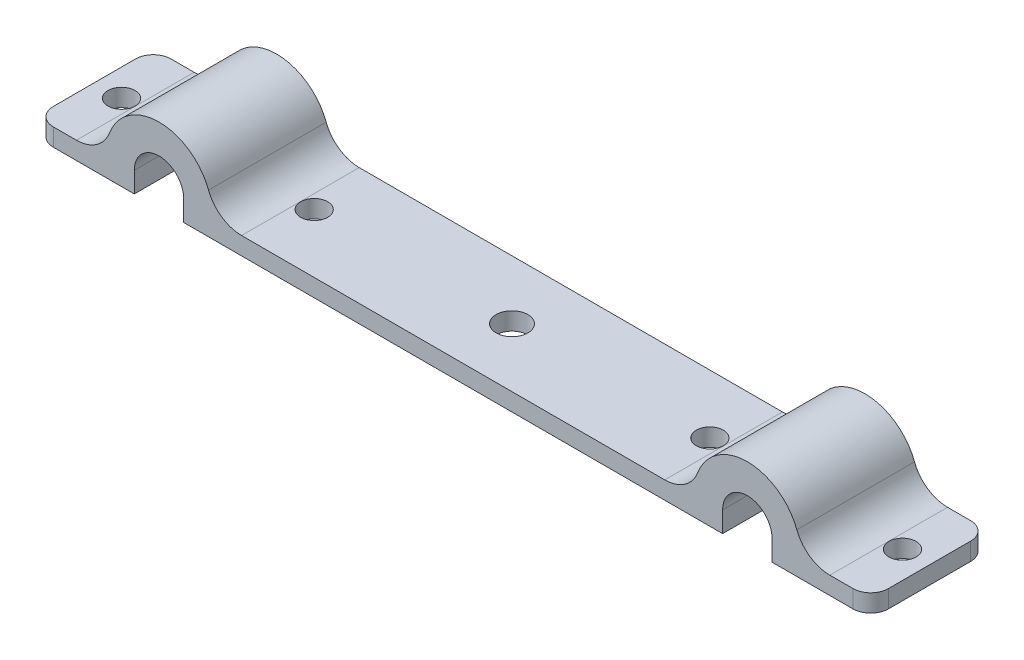
SolidWorks part; units mm, degrees
ref_plane "前视基准面" through (0, 0, 0) normal (0, 0, 1) x (1, 0, 0)
ref_plane "上视基准面" through (0, 0, 0) normal (0, 1, 0) x (1, 0, 0)
ref_plane "右视基准面" through (0, 0, 0) normal (1, 0, 0) x (0, 0, -1)
sketch "草图1" plane through (0, 0, 0) normal (0, 0, 1) x (1, 0, 0)
  line L0 (-1000, 0) -> (49000, 0) construction
  line L1 (0, -1000) -> (0, 49000) construction
  line L2 (54.2, 3.8) -> (54.2, 0.3)
  line L3 (54.2, 0.3) -> (70.9727, 0.3)
  line L4 (70.9727, 0.3) -> (70.9727, 3.3)
  line L5 (70.9727, 3.3) -> (64.0325, 3.3)
  line L6 (-35.9675, 3.3) -> (35.9675, 3.3)
  line L7 (-45.8, 0.3) -> (45.8, 0.3)
  line L8 (45.8, 0.3) -> (45.8, 3.8)
  line L9 (1000, 0) -> (-49000, 0) construction
  line L10 (-45.8, 0.3) -> (-45.8, 3.8)
  line L11 (-70.9727, 3.3) -> (-64.0325, 3.3)
  line L12 (-70.9727, 0.3) -> (-70.9727, 3.3)
  line L13 (-54.2, 0.3) -> (-70.9727, 0.3)
  line L14 (-54.2, 3.8) -> (-54.2, 0.3)
  circle A0 centre (50, 4) radius 4 construction
  arc A1 (54.2, 3.8) -> (45.8, 3.8) centre (50, 3.8) ccw
  circle A2 centre (-50, 4) radius 4 construction
  arc A3 (58.4195, 7.18) -> (41.5805, 7.18) centre (50, 4) ccw
  arc A4 (-58.4195, 7.18) -> (-41.5805, 7.18) centre (-50, 4) cw
  arc A5 (-54.2, 3.8) -> (-45.8, 3.8) centre (-50, 3.8) cw
  arc A6 (-41.5805, 7.18) -> (-35.9675, 3.3) centre (-35.9675, 9.3) ccw
  arc A7 (-58.4195, 7.18) -> (-64.0325, 3.3) centre (-64.0325, 9.3) cw
  arc A8 (35.9675, 3.3) -> (41.5805, 7.18) centre (35.9675, 9.3) ccw
  arc A9 (64.0325, 3.3) -> (58.4195, 7.18) centre (64.0325, 9.3) cw
  point P17 (0, 3.3)
  point P28 (0, 0.3)
  point P33 (-41.0273, 3.3)
  point P36 (-58.9727, 3.3)
  point P39 (41.0273, 3.3)
  point P42 (58.9727, 3.3)
  dimension "D1" = 8
  dimension "D2" = 8.4
  dimension "D3" = 9
  dimension "D8" = 6
  dimension "D4" = 0.3
  dimension "D5" = 3
  dimension "D6" = 12
  dimension "D7" = 100
  dimension "D9" = 20.9727
extrude "凸台-拉伸1" add sketch "草图1" along normal blind 20
fillet "圆角1" radius 3 4 edges at (70.9727, 1.8, 20) (70.9727, 1.8, 0) (-70.9727, 1.8, 0) (-70.9727, 1.8, 20)
sketch "草图2" plane through (0, 3.3, 0) normal (0, 1, 0) x (1, 0, 0)
  line L0 (0, -1000) -> (0, 49000) construction
  line L1 (35.9675, 0) -> (-35.9675, 0) construction
  line L2 (50, -1000) -> (50, 49000) construction
  line L3 (58.4195, 0) -> (41.5805, 0) construction
  line L5 (70.9727, -17) -> (70.9727, -3) construction
  circle A0 centre (0, -10) radius 2.7
  circle A1 centre (66.3727, -10) radius 2.3
  circle A2 centre (33.6273, -10) radius 2.3
  circle A3 centre (-33.6273, -10) radius 2.3
  circle A4 centre (-66.3727, -10) radius 2.3
  point P7 (0, 0)
  point P12 (50, 0)
  dimension "D1" = 5.4
  dimension "D3" = 4.6
  dimension "D2" = 10
  dimension "D4" = 4.6
extrude "切除-拉伸1" cut sketch "草图2" against normal through all and the other way through all
